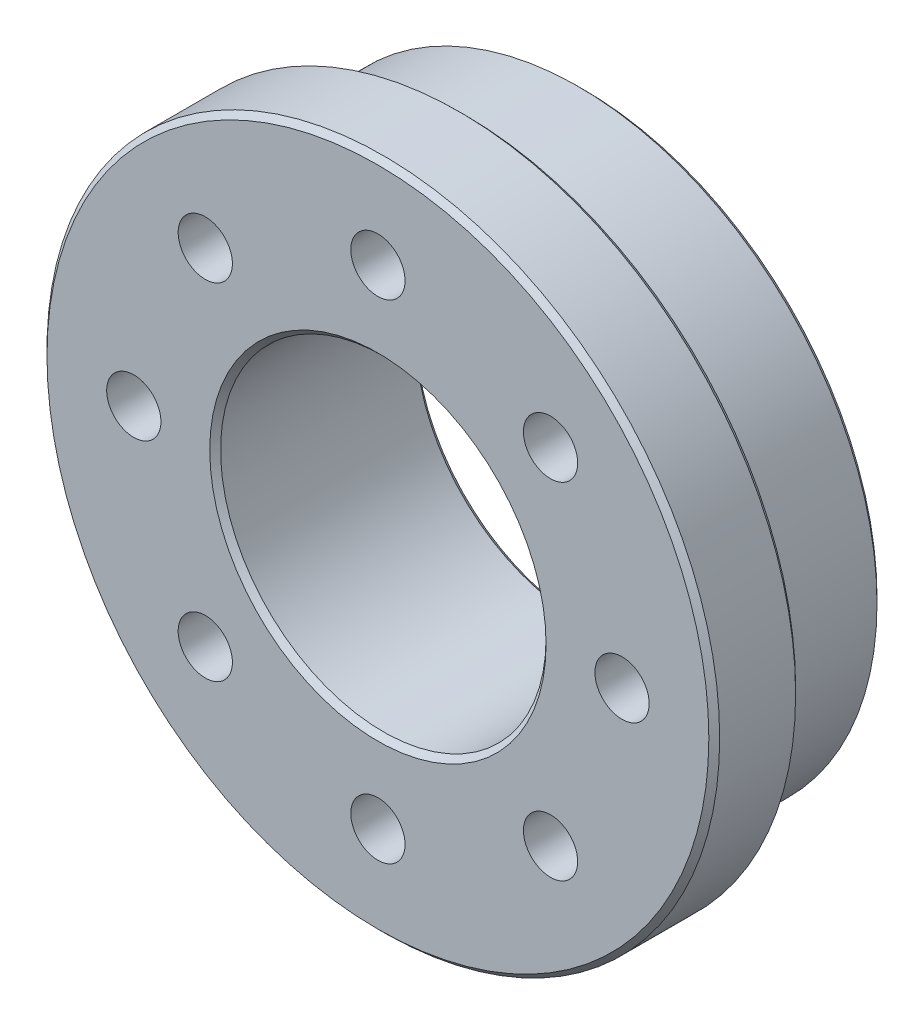
SolidWorks part; units mm, degrees
ref_plane "前视基准面" through (0, 0, 0) normal (0, 0, 1) x (1, 0, 0)
ref_plane "上视基准面" through (0, 0, 0) normal (0, 1, 0) x (1, 0, 0)
ref_plane "右视基准面" through (0, 0, 0) normal (1, 0, 0) x (0, 0, -1)
sketch "草图1" plane through (0, 0, 0) normal (0, 0, 1) x (1, 0, 0)
  circle A0 centre (0, 0) radius 27.5
extrude "拉伸1" add sketch "草图1" along normal blind 11
sketch "草图2" plane through (0, 0, 11) normal (0, 0, 1) x (1, 0, 0)
  circle A0 centre (0, 0) radius 31
extrude "拉伸2" add sketch "草图2" along normal blind 8
sketch "草图3" plane through (0, 0, 19) normal (0, 0, 1) x (1, 0, 0)
  circle A1 centre (0, 22.5) radius 2.5
  circle A2 centre (15.9099, 15.9099) radius 2.5
  circle A3 centre (22.5, 0) radius 2.5
  circle A4 centre (15.9099, -15.9099) radius 2.5
  circle A5 centre (0, -22.5) radius 2.5
  circle A6 centre (-15.9099, -15.9099) radius 2.5
  circle A7 centre (-22.5, 0) radius 2.5
  circle A8 centre (-15.9099, 15.9099) radius 2.5
extrude "切除-拉伸1" cut sketch "草图3" against normal blind 15
sketch "草图4" plane through (0, 0, 19) normal (0, 0, 1) x (1, 0, 0)
  circle A0 centre (0, 0) radius 15
  dimension "D1" = 30
extrude "切除-拉伸2" cut sketch "草图4" against normal through all
chamfer "倒角1" distance 0.5 angle 45 4 edges at (31, 0, 19) (31, 0, 11) (15, 0, 0) (27.5, 0, 0)
chamfer "倒角2" distance 0.5 angle 45 1 edges at (15, 0, 19)
